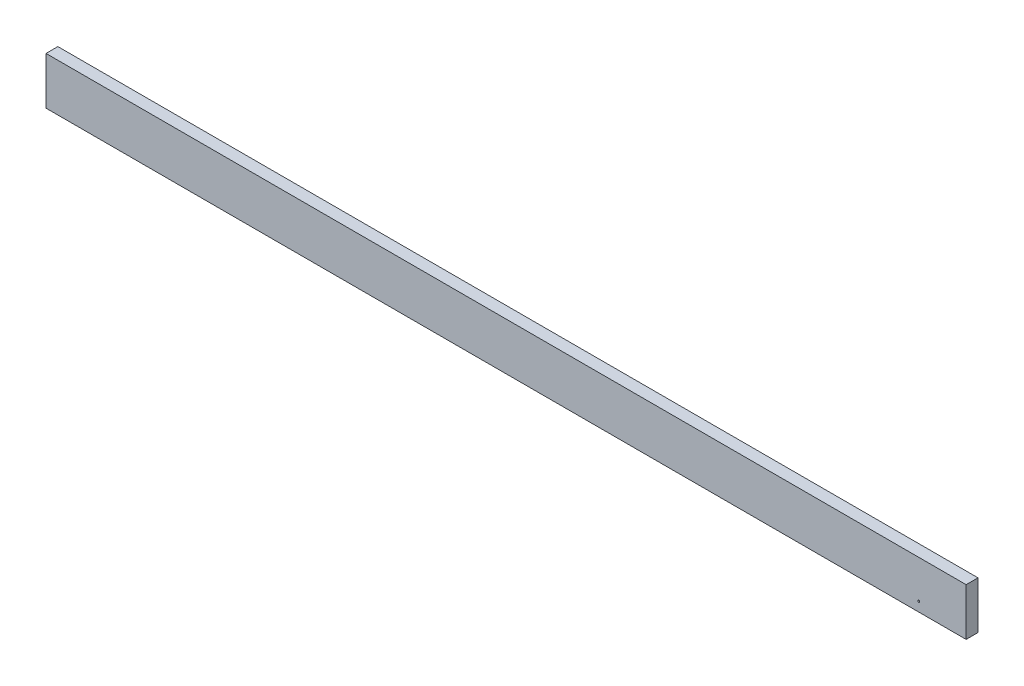
SolidWorks part; units mm, degrees
material "Oak"
ref_plane "Piano frontale" through (0, 0, 0) normal (0, 0, 1) x (1, 0, 0)
ref_plane "Piano superiore" through (0, 0, 0) normal (0, 1, 0) x (1, 0, 0)
ref_plane "Piano destro" through (0, 0, 0) normal (1, 0, 0) x (0, 0, -1)
sketch "Sketch1" plane through (0, 0, 0) normal (0, 0, 1) x (1, 0, 0)
  line L1 (0, 0) -> (194, 0)
  line L2 (0, 0) -> (0, 10)
  line L3 (0, 10) -> (194, 10)
  line L4 (194, 0) -> (194, 10)
  dimension "D1" = 194
  dimension "D2" = 10
extrude "Boss-Extrude1" add sketch "Sketch1" along normal blind 2.5
scale "Scale1" scale about origin uniform scaling yes scale factor 10
hole_wizard "#6 Clearance Hole2" positions "Sketch6" profile "Sketch7" hole size "#6" standard "ANSI Inch"
sketch "Sketch6" plane through (2049.4185, 550, 0) normal (0, 0, -1) x (-1, 0, 0)
  point P0 (209.4185, -530.1945)
sketch "Sketch7" plane through (1840, 19.8055, 0) normal (1, 0, 0) x (0, 1, 0)
  line L0 (0, 0) -> (0, 49)
  line L1 (0, 49) -> (1.905, 49)
  line L2 (1.905, 49) -> (1.905, 0)
  line L5 (1.905, 0) -> (0, 0)
  line L11 (0, -6.35) -> (0, 107.95) construction
  dimension "Thru Hole Dia." = 3.81
  dimension "Thru Hole Depth" = 49
